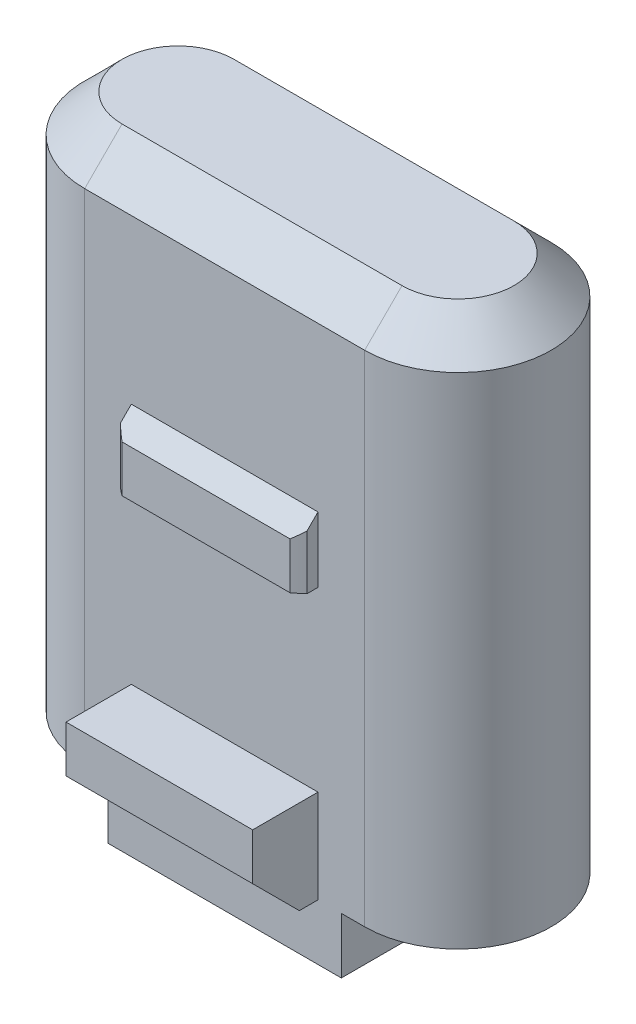
SolidWorks part; units mm, degrees
ref_plane "前视基准面" through (0, 0, 0) normal (0, 0, 1) x (1, 0, 0)
ref_plane "上视基准面" through (0, 0, 0) normal (0, 1, 0) x (1, 0, 0)
ref_plane "右视基准面" through (0, 0, 0) normal (1, 0, 0) x (0, 0, -1)
other "Configuration Table"
sketch "草图2" plane through (0, 0, 0) normal (0, 1, 0) x (1, 0, 0)
  line L0 (0, 0) -> (6, 0) construction
  line L1 (0, 2) -> (6, 2)
  line L2 (0, -2) -> (6, -2)
  arc A0 (0, 2) -> (0, -2) centre (0, 0) ccw
  arc A1 (6, -2) -> (6, 2) centre (6, 0) ccw
  point P3 (3, 0)
  dimension "D2" = 2
  dimension "D1" = 6
extrude "凸台-拉伸1" add sketch "草图2" along normal blind 12.7
sketch "草图3" plane through (0, 0, 2) normal (0, 0, 1) x (1, 0, 0)
  line L0 (-2, 0) -> (0, 0) construction
  line L1 (-2, 0) -> (0.5, 0)
  line L2 (-2, 0) -> (-2, 1.2)
  line L3 (-2, 1.2) -> (0.5, 1.2)
  line L4 (0.5, 0) -> (0.5, 1.2)
  line L5 (-2, 0) -> (0.5, 1.2) construction
  line L6 (-2, 1.2) -> (0.5, 0) construction
  line L7 (3, 12.7) -> (3, 0) construction
  line L8 (8, 0) -> (5.5, 0)
  line L9 (8, 0) -> (8, 1.2)
  line L10 (8, 1.2) -> (5.5, 1.2)
  line L11 (5.5, 0) -> (5.5, 1.2)
  line L12 (8, 0) -> (5.5, 1.2) construction
  line L13 (8, 1.2) -> (5.5, 0) construction
  line L14 (0, 12.7) -> (6, 12.7) construction
  line L15 (0, 0) -> (6, 0) construction
  line L16 (-2, 12.7) -> (-2, 0) construction
  point P4 (-0.75, 0.6)
  point P11 (6.75, 0.6)
  dimension "D1" = 1.2
  dimension "D2" = 2.5
extrude "切除-拉伸1" cut sketch "草图3" against normal up to next
ref_plane "基准面1" through (3, 0, 0) normal (-1, 0, 0) x (0, 0, 1)
sketch "草图5" plane through (3, 0, 0) normal (-1, 0, 0) x (0, 0, 1)
  line L0 (-2, 7) -> (-2.4, 7)
  line L1 (-2, 12.7) -> (-2, 1.2) construction
  line L2 (-2.4, 7) -> (-2.4, 8)
  line L3 (-2.4, 8) -> (-2, 8.4)
  line L4 (-2, 8.4) -> (-2, 7)
  line L5 (-2, 0) -> (2, 0) construction
  line L6 (0, 1.2) -> (0, 12.7) construction
  line L7 (-2, 1.2) -> (2, 1.2) construction
  line L8 (2, 12.7) -> (-2, 12.7) construction
  line L9 (2, 8.4) -> (2, 7)
  line L10 (2.4, 8) -> (2, 8.4)
  line L11 (2.4, 7) -> (2.4, 8)
  line L12 (2, 7) -> (2.4, 7)
  line L14 (-2, 1.2) -> (-3.4, 1.2)
  line L15 (-2, 1.2) -> (-2, 3.2)
  line L16 (-2, 3.2) -> (-3.4, 3.2)
  line L17 (-3.4, 1.2) -> (-3.4, 3.2)
  line L18 (-2, 1.2) -> (-3.4, 3.2) construction
  line L19 (-2, 3.2) -> (-3.4, 1.2) construction
  line L24 (2, 3.2) -> (3.4, 1.2) construction
  line L25 (2, 1.2) -> (3.4, 3.2) construction
  line L26 (3.4, 1.2) -> (3.4, 3.2)
  line L27 (2, 3.2) -> (3.4, 3.2)
  line L28 (2, 1.2) -> (2, 3.2)
  line L29 (2, 1.2) -> (3.4, 1.2)
  point P22 (-2.7, 2.2)
  point P27 (2.7, 2.2)
  dimension "D1" = 7
  dimension "D2" = 0.4
  dimension "D3" = 1
  dimension "D4" = 45
  dimension "D5" = 1.4
  dimension "D6" = 3.2
  dimension "D7" = 2
extrude "凸台-拉伸2" add sketch "草图5" along normal blind 2 and the other way blind 2
sketch "草图6" plane through (0, 12.7, 0) normal (0, 1, 0) x (1, 0, 0)
  line L0 (3, 0.66) -> (3, -0.66) construction
  line L1 (1.2, 2.4) -> (1, 2.4)
  line L2 (4.8, -2.4) -> (5, -2.4)
  line L5 (5, 2.4) -> (1, 2.4)
  line L6 (1, 2.4) -> (1, 2)
  line L7 (1, 2) -> (5, 2)
  line L8 (5, 2) -> (5, 2.4)
  line L9 (5, 2.4) -> (4.8, 2.4)
  line L10 (1, 2.4) -> (1, 2.2361)
  line L12 (5, 2.2361) -> (5, 2.4)
  line L13 (5, -2) -> (1, -2)
  line L14 (1, -2) -> (1, -2.4)
  line L15 (1, -2.4) -> (5, -2.4)
  line L16 (5, -2.4) -> (5, -2)
  line L18 (1, -2.2361) -> (1, -2.4)
  line L19 (1, -2.4) -> (1.2, -2.4)
  line L20 (5, -2.4) -> (5, -2.2361)
  arc A0 (1, -2.2361) -> (1.2, -2.4) centre (3, 0) ccw
  arc A1 (5, 2.2361) -> (4.8, 2.4) centre (3, 0) ccw
  arc A2 (1.2, 2.4) -> (1, 2.2361) centre (3, 0) ccw
  arc A3 (4.8, -2.4) -> (5, -2.2361) centre (3, 0) ccw
  dimension "D1" = 6
  dimension "D2" = 0
  dimension "D3" = 0
extrude "切除-拉伸2" cut sketch "草图6" against normal up to next
chamfer "倒角1" distance 1 angle 45 2 edges at (3, 1.2, 3.4) (3, 1.2, -3.4)
chamfer "倒角2" distance 0.8 angle 45 4 edges at (8, 12.7, 0) (3, 12.7, -2) (3, 12.7, 2) (-2, 12.7, 0)
